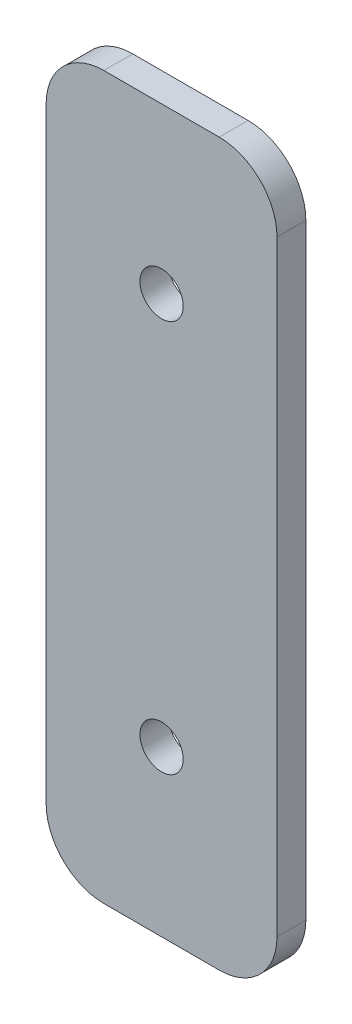
SolidWorks part; units mm, degrees
ref_plane "Ebene vorne" through (0, 0, 0) normal (0, 0, 1) x (1, 0, 0)
ref_plane "Ebene oben" through (0, 0, 0) normal (0, 1, 0) x (1, 0, 0)
ref_plane "Ebene rechts" through (0, 0, 0) normal (1, 0, 0) x (0, 0, -1)
sketch "Skizze1" plane through (0, 0, 0) normal (0, 0, 1) x (1, 0, 0)
  line L0 (39.387, 0) -> (-51.4047, 0) construction
  line L1 (-20, 62.5) -> (20, 62.5)
  line L2 (-20, 62.5) -> (-20, -62.5)
  line L3 (-20, -62.5) -> (20, -62.5)
  line L4 (20, 62.5) -> (20, -62.5)
  circle A0 centre (0, 34) radius 3.75
  circle A1 centre (0, -34) radius 3.75
  point P4 (0, 62.5)
  point P5 (-20, 0)
  dimension "D3" = 34
  dimension "D4" = 7.5
  dimension "D1" = 62.5
  dimension "D2" = 20
extrude "Aufsatz-Linear austragen1" add sketch "Skizze1" along normal blind 5
fillet "Verrundung1" radius 10 4 edges at (-20, 62.5, 2.5) (-20, -62.5, 2.5) (20, -62.5, 2.5) (20, 62.5, 2.5)
